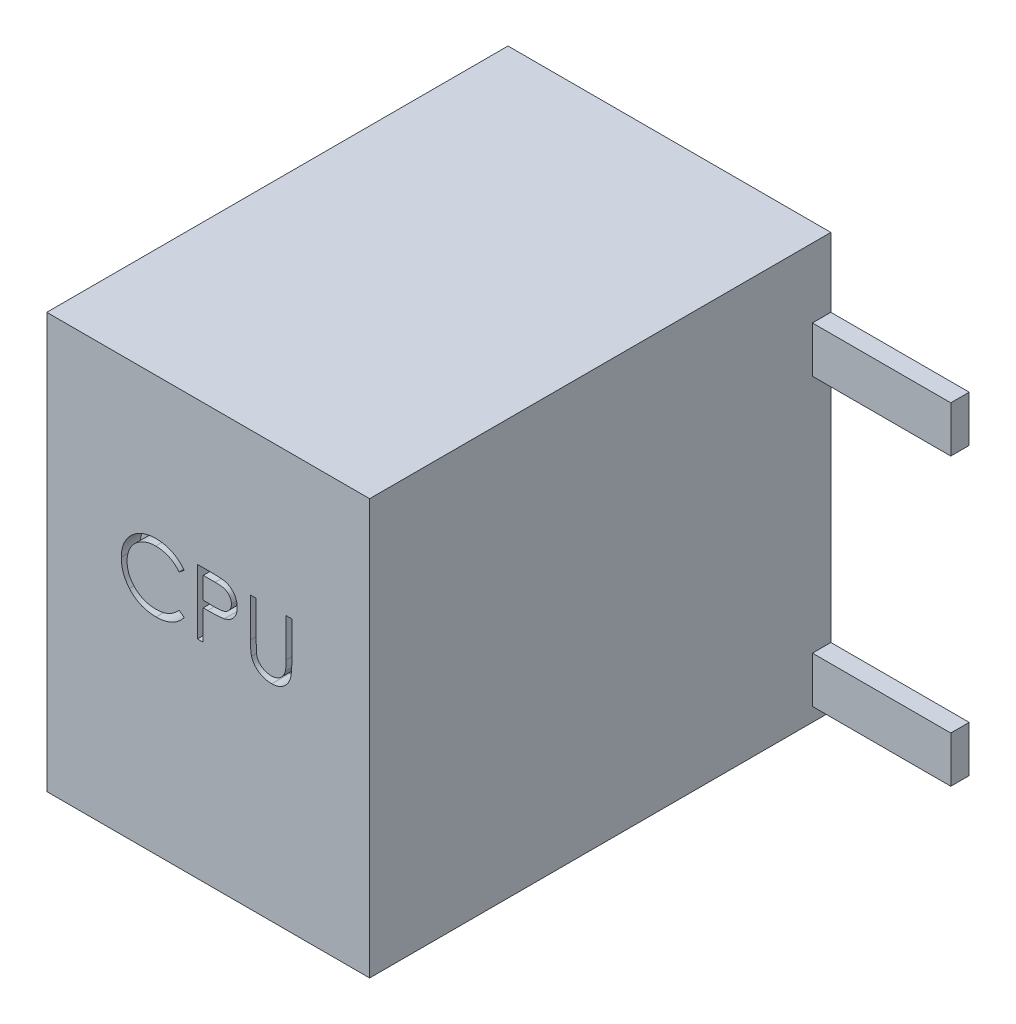
SolidWorks part; units mm, degrees
ref_plane "Front Plane" through (0, 0, 0) normal (0, 0, 1) x (1, 0, 0)
ref_plane "Top Plane" through (0, 0, 0) normal (0, 1, 0) x (1, 0, 0)
ref_plane "Right Plane" through (0, 0, 0) normal (1, 0, 0) x (0, 0, -1)
sketch "Sketch1" plane through (0, 0, 0) normal (0, 0, 1) x (1, 0, 0)
  line L1 (8.75, -11.25) -> (-8.75, -11.25)
  line L2 (8.75, -11.25) -> (8.75, 11.25)
  line L3 (8.75, 11.25) -> (-8.75, 11.25)
  line L4 (-8.75, -11.25) -> (-8.75, 11.25)
  line L5 (8.75, -11.25) -> (-8.75, 11.25) construction
  line L6 (8.75, 11.25) -> (-8.75, -11.25) construction
  point P0 (0, 0)
  dimension "D1" = 17.5
  dimension "D2" = 22.5
extrude "Boss-Extrude1" add sketch "Sketch1" along normal mid plane 25
sketch "Sketch2" plane through (0, 0, 12.5) normal (0, 0, 1) x (1, 0, 0)
  line L1 (-8.75, 0) -> (8.75, 0) construction
  line L2 (-8.75, 11.25) -> (-8.75, -11.25) construction
  line L3 (8.75, -11.25) -> (8.75, 11.25) construction
  text T0 "CPU"
extrude "Cut-Extrude1" cut sketch "Sketch2" against normal blind 1
sketch "Sketch3" plane through (0, 0, -12.5) normal (0, 0, -1) x (-1, 0, 0)
  line L0 (8.75, -11.25) -> (-8.75, -11.25) construction
  line L1 (-1.25, -11.25) -> (1.25, -11.25)
  line L2 (-1.25, -11.25) -> (-1.25, -18.75)
  line L3 (-1.25, -18.75) -> (1.25, -18.75)
  line L4 (1.25, -11.25) -> (1.25, -18.75)
  line L5 (-8.75, -11.25) -> (-8.75, 11.25) construction
  line L6 (-8.75, 7.5) -> (-16.25, 7.5)
  line L7 (-8.75, 7.5) -> (-8.75, 5)
  line L8 (-8.75, 5) -> (-16.25, 5)
  line L9 (-16.25, 7.5) -> (-16.25, 5)
  line L10 (-8.75, 11.25) -> (8.75, 11.25) construction
  line L12 (-8.75, -10.5) -> (-16.25, -10.5)
  line L13 (-8.75, -10.5) -> (-8.75, -8)
  line L14 (-8.75, -8) -> (-16.25, -8)
  line L15 (-16.25, -10.5) -> (-16.25, -8)
  point P6 (0, -11.25)
  point P14 (-8.75, 6.25)
  dimension "D1" = 2.5
  dimension "D2" = 7.5
  dimension "D3" = 2.5
  dimension "D4" = 5
  dimension "D5" = 7.5
  dimension "D6" = 7.5
  dimension "D7" = 0.75
  dimension "D8" = 2.5
extrude "Boss-Extrude2" add sketch "Sketch3" against normal blind 1
